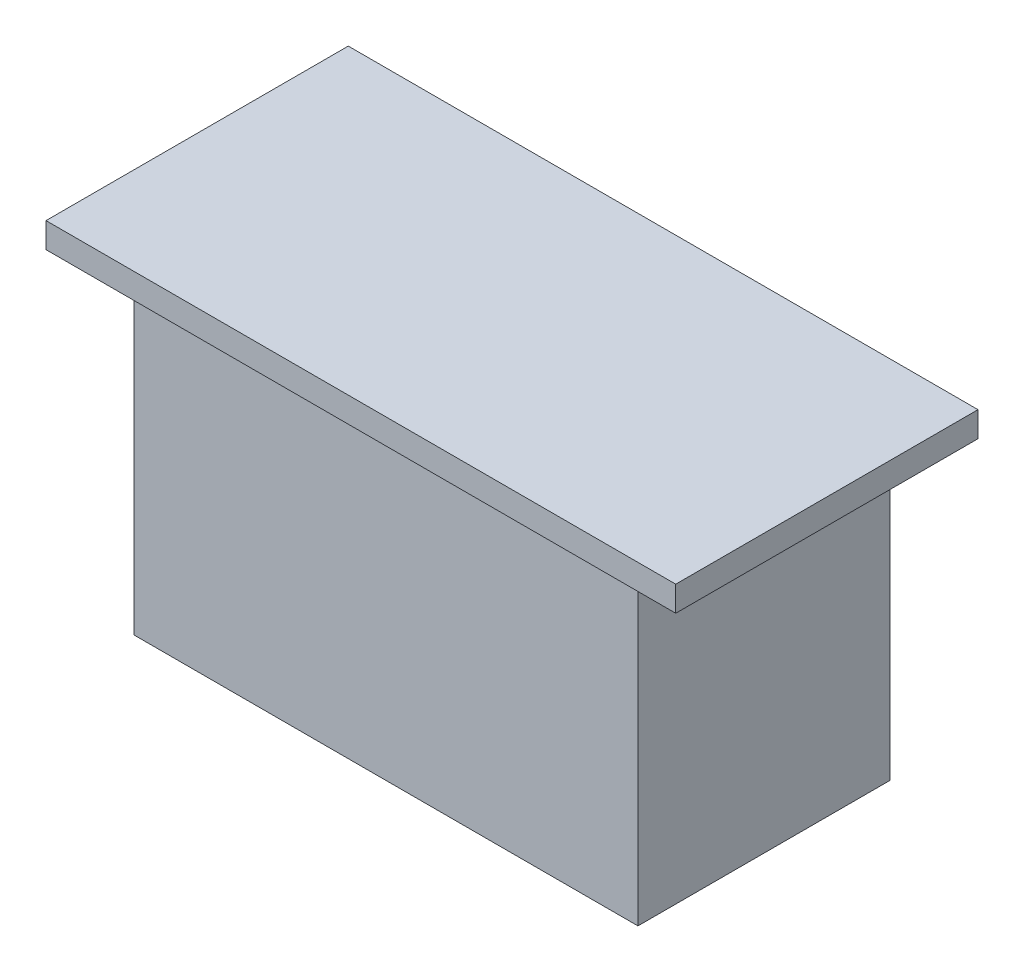
SolidWorks part; units mm, degrees
ref_plane "Front Plane" through (0, 0, 0) normal (0, 0, 1) x (1, 0, 0)
ref_plane "Top Plane" through (0, 0, 0) normal (0, 1, 0) x (1, 0, 0)
ref_plane "Right Plane" through (0, 0, 0) normal (1, 0, 0) x (0, 0, -1)
sketch "Sketch1" plane through (0, 0, 0) normal (0, 1, 0) x (1, 0, 0)
  line L1 (-9.8185, 5.9827) -> (15.5815, 5.9827)
  line L2 (-9.8185, 5.9827) -> (-9.8185, -6.7173)
  line L3 (-9.8185, -6.7173) -> (15.5815, -6.7173)
  line L4 (15.5815, 5.9827) -> (15.5815, -6.7173)
  dimension "D1" = 25.4
  dimension "D2" = 12.7
extrude "Boss-Extrude1" add sketch "Sketch1" along normal blind 15.875 contours L2 L3 L4 L1
sketch "Sketch2" plane through (0, 15.875, 0) normal (0, 1, 0) x (1, 0, 0)
  line L0 (-12.9935, -7.9873) -> (18.7565, -7.9873)
  line L1 (-12.9935, -7.9873) -> (-12.9935, 7.2527)
  line L2 (18.7565, -7.9873) -> (18.7565, 7.2527)
  line L3 (-12.9935, 7.2527) -> (18.7565, 7.2527)
  line L4 (-12.9935, -7.9873) -> (18.7565, 7.2527) construction
  line L5 (18.7565, -7.9873) -> (-12.9935, 7.2527) construction
  line L6 (15.5815, 5.9827) -> (15.5815, -6.7173) construction
  line L7 (-9.8185, 5.9827) -> (15.5815, 5.9827) construction
  point P1 (2.8815, -0.3673)
  dimension "D1" = 15.24
  dimension "D2" = 31.75
  dimension "D3" = 12.7
  dimension "D4" = 6.35
extrude "Boss-Extrude2" add sketch "Sketch2" along normal blind 1.27
